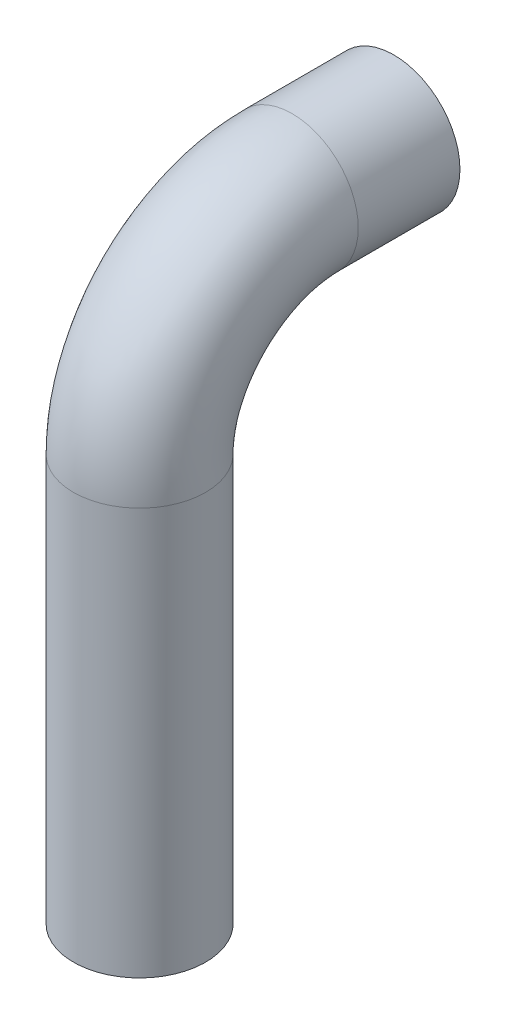
SolidWorks part; units mm, degrees
ref_plane "Front Plane" through (0, 0, 0) normal (0, 0, 1) x (1, 0, 0)
ref_plane "Top Plane" through (0, 0, 0) normal (0, 1, 0) x (1, 0, 0)
ref_plane "Right Plane" through (0, 0, 0) normal (1, 0, 0) x (0, 0, -1)
sketch "Sketch1" plane through (0, 0, 0) normal (1, 0, 0) x (0, 0, -1)
  line L0 (0, 33.4567) -> (-20, 33.4567)
  line L2 (0, 55) -> (0, -55) construction
  line L3 (-50, 3.4567) -> (-50, -76.5433)
  arc A0 (-20, 33.4567) -> (-50, 3.4567) centre (-20, 3.4567) ccw
  dimension "D2" = 30
  dimension "D1" = 20
  dimension "D3" = 110
sketch "Sketch2" plane through (0, 0, 0) normal (0, 0, 1) x (1, 0, 0)
  line L0 (0, 3.4567) -> (0, 33.4567) construction
  circle A0 centre (0, 33.4567) radius 10
  point P6 (0, 0)
  dimension "D1" = 20
sweep "Sweep-Thin1" add profiles "Sketch2" path "Sketch1" parameters "D1"=3
